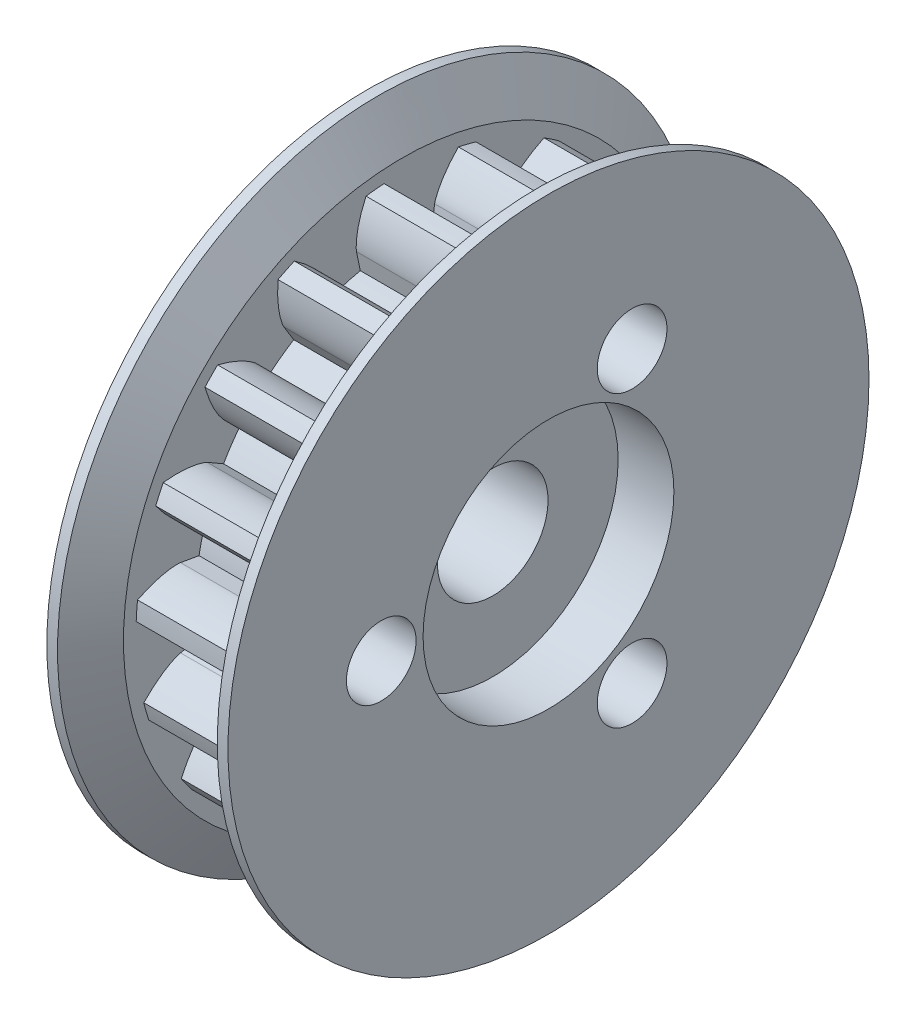
SolidWorks part; units mm, degrees
material "ABS"
ref_plane "Front Plane" through (0, 0, 0) normal (1, 0, 0) x (0, 1, 0)
ref_plane "Top Plane" through (0, 0, 0) normal (0, 0, 1) x (0, 1, 0)
ref_plane "Right Plane" through (0, 0, 0) normal (0, 1, 0) x (-1, 0, 0)
sketch "Sketch1" plane through (0, 0, 0) normal (1, 0, 0) x (0, 1, 0)
  circle A0 centre (0, 0) radius 9.5493
  circle A1 centre (0, 0) radius 8.0761 construction
  circle A2 centre (0, 0) radius 7.4007 construction
  circle A3 centre (0, 0) radius 8.5944 construction
  dimension "D1" = 19.0986
  dimension "D2" = 16.1521
  dimension "D3" = 14.8014
  dimension "D4" = 17.1887
extrude "Boss-Extrude1" add sketch "Sketch1" along normal blind 4
sketch "Sketch3" plane through (4, 0, 0) normal (1, 0, 0) x (0, 1, 0)
  line L0 (0, 0) -> (8.0761, 0) construction
  line L1 (0, 0) -> (8.5934, 0.1281) construction
  line L2 (0, 0) -> (8.5719, -0.6214) construction
  line L3 (8.5719, -0.6214) -> (8.0549, -0.5839)
  line L4 (8.5719, -0.6214) -> (11.1593, -0.8089)
  line L5 (11.1593, 2.4323) -> (11.1593, -0.8089)
  line L6 (8.0761, 0) -> (7.4007, 0)
  line L7 (8.0549, -0.5839) -> (7.3813, -0.5351)
  circle A0 centre (0, 0) radius 8.5944 construction
  circle A1 centre (0, 0) radius 8.0761 construction
  circle A2 centre (0, 0) radius 7.4007 construction
  arc A3 (7.4007, 0) -> (7.3813, -0.5351) centre (0, 0) cw
  spline S0 degree 4 poles (8.0761, 0) (8.082, 0.0001) (8.0988, 0.0009) (8.1303, 0.0038) (8.1816, 0.0108) (8.2466, 0.0229) (8.3299, 0.0423) (8.4272, 0.0697) (8.5329, 0.1046) (8.6464, 0.1478) (8.7583, 0.1954) (8.8684, 0.247) (8.9767, 0.3022) (9.1061, 0.3733) (9.2586, 0.4645) (9.4328, 0.5796) (9.6251, 0.7199) (9.8152, 0.8732) (9.9971, 1.0323) (10.1746, 1.2022) (10.3418, 1.373) (10.5085, 1.5593) (10.6589, 1.7358) (10.8191, 1.9429) (10.9461, 2.1127) (11.1045, 2.3463) (11.1952, 2.487) (11.2982, 2.6548) (11.3422, 2.731) (11.3694, 2.7778) knots 0 0 0 0 0 0.005377 0.015084 0.028532 0.04661 0.064855 0.092111 0.119476 0.146842 0.174209 0.201575 0.228941 0.256307 0.307035 0.361767 0.4165 0.471232 0.525964 0.580697 0.635429 0.690161 0.744894 0.799626 0.854358 0.909091 0.954545 1 1 1 1 1 construction
  spline S1 degree 4 poles (8.0761, 0) (8.082, 0.0001) (8.0988, 0.0009) (8.1303, 0.0038) (8.1816, 0.0108) (8.2466, 0.0229) (8.3299, 0.0423) (8.4272, 0.0697) (8.5329, 0.1046) (8.6464, 0.1478) (8.7583, 0.1954) (8.8684, 0.247) (8.9767, 0.3022) (9.1061, 0.3733) (9.2586, 0.4645) (9.4328, 0.5796) (9.6251, 0.7199) (9.8152, 0.8732) (9.9971, 1.0323) (10.1746, 1.2022) (10.3418, 1.373) (10.5085, 1.5593) (10.6589, 1.7358) (10.8191, 1.9429) (10.9461, 2.1127) (11.0701, 2.2957) (11.1294, 2.3858) (11.1593, 2.4323) knots 0 0 0 0 0 0.005377 0.015084 0.028532 0.04661 0.064855 0.092111 0.119476 0.146842 0.174209 0.201575 0.228941 0.256307 0.307035 0.361767 0.4165 0.471232 0.525964 0.580697 0.635429 0.690161 0.744894 0.799626 0.854358 0.909091 0.909091 0.909091 0.909091 0.909091
  dimension "D1" = 5
extrude "Cut-Extrude1" cut sketch "Sketch3" against normal through all
mirror "Mirror1" about plane through (0, 8.5719, -0.6214) normal (0, -0.0723, -0.9974) of "Cut-Extrude1"
pattern_circular "CirPattern6" count 18 over 360 about axis through (4, 0, 0) along (-1, 0, 0) of "Cut-Extrude1", "Mirror1"
sketch "Sketch4" plane through (0, 0, 0) normal (0, 1, 0) x (-1, 0, 0)
  line L0 (-9.291, 0) -> (5.5255, 0) construction
  line L1 (-4, 0) -> (-4, 10)
  line L2 (-4, 10) -> (-4.866, 11.5)
  line L3 (-4.866, 11.5) -> (-5.25, 11.5)
  line L4 (-5.25, 11.5) -> (-5.25, 0)
  line L5 (-5.25, 0) -> (-4, 0)
  line L6 (0, 0) -> (1.25, 0)
  line L7 (1.25, 0) -> (1.25, 11.5)
  line L8 (1.25, 11.5) -> (0.866, 11.5)
  line L9 (0.866, 11.5) -> (0, 10)
  line L10 (0, 10) -> (0, 0)
  dimension "D1" = 150
  dimension "D2" = 150
  dimension "D3" = 10
  dimension "D4" = 1.25
  dimension "D5" = 1.5
revolve "Revolve1" add sketch "Sketch4" angle 360 about L0
sketch "Sketch5" plane through (5.25, 0, 0) normal (1, 0, 0) x (0, 1, 0)
  circle A0 centre (0, 0) radius 4.5
  circle A1 centre (0, 0) radius 7.5
  dimension "D1" = 9
  dimension "D2" = 15
sketch "Sketch6" plane through (5.25, 0, 0) normal (1, 0, 0) x (0, 1, 0)
  circle A0 centre (0, 0) radius 1.9844
  dimension "D1" = 3.9688
extrude "Cut-Extrude2" cut sketch "Sketch6" against normal through all
sketch "Sketch7" plane through (-1.25, 0, 0) normal (-1, 0, 0) x (0, -1, 0)
  line L0 (0, 6) -> (-5.1962, -3) construction
  line L1 (-5.1962, -3) -> (5.1962, -3) construction
  line L2 (5.1962, -3) -> (0, 6) construction
  circle A0 centre (0, 0) radius 6 construction
  point P3 (0, 6)
  point P4 (-5.1962, -3)
  point P5 (5.1962, -3)
  dimension "D1" = 12
hole_wizard "Hole4" positions "Sketch11" profile "Sketch12" legacy end condition through all
sketch "Sketch11" plane through (-1.25, 0, 0) normal (-1, 0, 0) x (0, 0, 1)
  point P0 (-3, 5.1962)
  point P3 (-3, -5.1962)
  point P6 (6, 0)
sketch "Sketch12" plane through (-1.25, 5.1962, -3) normal (0, 1, 0) x (0, 0, 1)
  line L0 (0, 0) -> (0, 6.5)
  line L1 (0, 6.5) -> (1.25, 6.5)
  line L2 (1.25, 6.5) -> (1.25, 1)
  line L3 (1.25, 1) -> (1.75, 1)
  line L4 (1.75, 1) -> (1.75, 0)
  line L5 (1.75, 0) -> (0, 0)
  line L6 (0, 110) -> (0, -10) construction
  dimension "Diameter" = 2.5
  dimension "Depth" = 6.5
  dimension "C-Bore Diameter" = 3.5
  dimension "C-Bore Depth" = 1
extrude "Cut-Extrude3" cut sketch "Sketch5" against normal blind 2 contours A0
equation "\"DiametralPitch\"= pi / \"Pitch\""
equation "\"NumberTeeth\"= 18"
equation "\"PressureAngle\"= 20"
equation "\"PitchDiameter\"= \"NumberTeeth\" / \"DiametralPitch\""
equation "\"BaseDiameter\"= \"PitchDiameter\" * cos ( \"PressureAngle\" )"
equation "\"Addendum\"= 1 / \"DiametralPitch\""
equation "\"Dedendum\"= 1.25 / \"DiametralPitch\""
equation "\"AddendumDiameter\"= \"PitchDiameter\" + \"Addendum\" + \"Addendum\""
equation "\"DedendumDiameter\"= \"PitchDiameter\" - \"Dedendum\" - \"Dedendum\""
equation "\"ToothSpacing\"= 360 / ( 4 * \"NumberTeeth\" )"
equation "\"D1@Sketch1\"=\"AddendumDiameter\""
equation "\"D2@Sketch1\"=\"BaseDiameter\""
equation "\"D3@Sketch1\"=\"DedendumDiameter\""
equation "\"D4@Sketch1\"=\"PitchDiameter\""
equation "\"D1@Sketch3\"=\"ToothSpacing\""
equation "\"D1@CirPattern6\"=\"NumberTeeth\""
equation "\"Pitch\"= 3"
equation "\"D1@Sketch6\"=5/32*25.4"
